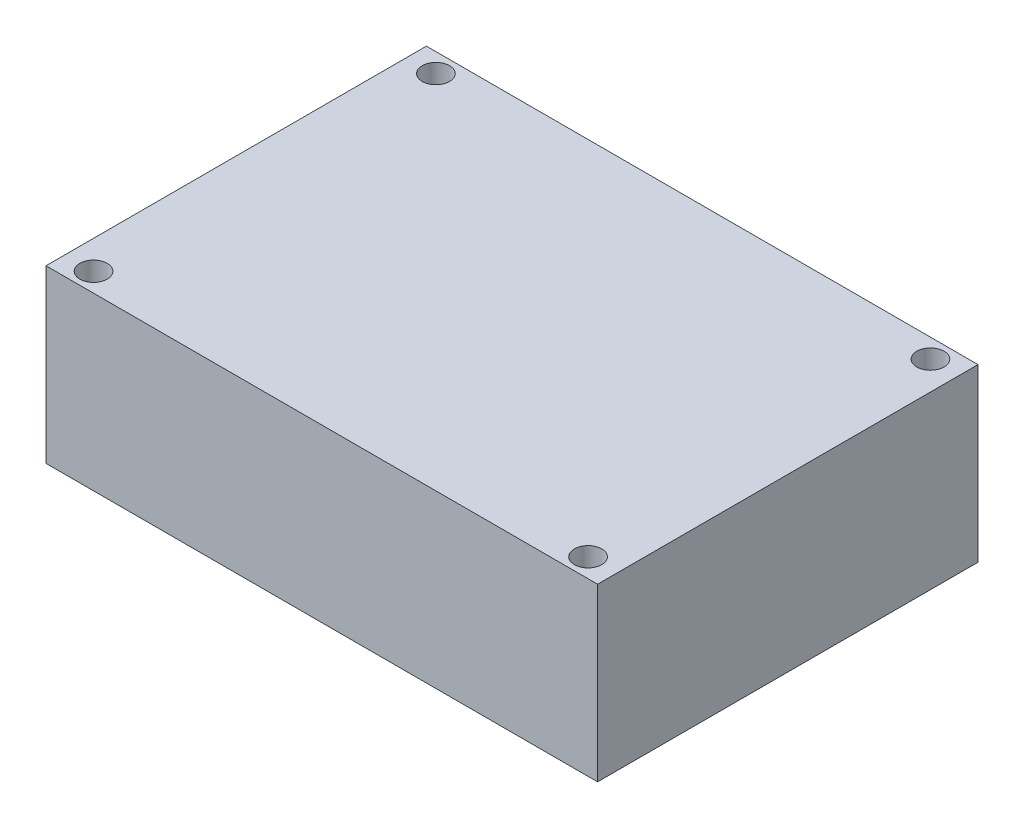
SolidWorks part; units mm, degrees
ref_plane "Front Plane" through (0, 0, 0) normal (0, 0, 1) x (1, 0, 0)
ref_plane "Top Plane" through (0, 0, 0) normal (0, 1, 0) x (1, 0, 0)
ref_plane "Right Plane" through (0, 0, 0) normal (1, 0, 0) x (0, 0, -1)
sketch "Sketch1" plane through (0, 0, 0) normal (0, 1, 0) x (1, 0, 0)
  line L1 (-36.83, -25.4) -> (36.83, -25.4)
  line L2 (-36.83, -25.4) -> (-36.83, 25.4)
  line L3 (-36.83, 25.4) -> (36.83, 25.4)
  line L4 (36.83, -25.4) -> (36.83, 25.4)
  line L5 (-36.83, -25.4) -> (36.83, 25.4) construction
  line L6 (-36.83, 25.4) -> (36.83, -25.4) construction
  line L7 (-33.02, -22.86) -> (33.02, -22.86) construction
  line L8 (-33.02, -22.86) -> (-33.02, 22.86) construction
  line L9 (-33.02, 22.86) -> (33.02, 22.86) construction
  line L10 (33.02, -22.86) -> (33.02, 22.86) construction
  line L11 (-33.02, -22.86) -> (33.02, 22.86) construction
  line L12 (-33.02, 22.86) -> (33.02, -22.86) construction
  circle A0 centre (-33.02, 22.86) radius 1.8288
  circle A1 centre (33.02, 22.86) radius 1.8288
  circle A2 centre (33.02, -22.86) radius 1.8288
  circle A3 centre (-33.02, -22.86) radius 1.8288
  point P0 (0, 0)
  point P6 (0, 0)
  dimension "D5" = 3.6576
  dimension "D1" = 73.66
  dimension "D2" = 50.8
  dimension "D3" = 66.04
  dimension "D4" = 45.72
extrude "Boss-Extrude1" add sketch "Sketch1" along normal mid plane 22.86
